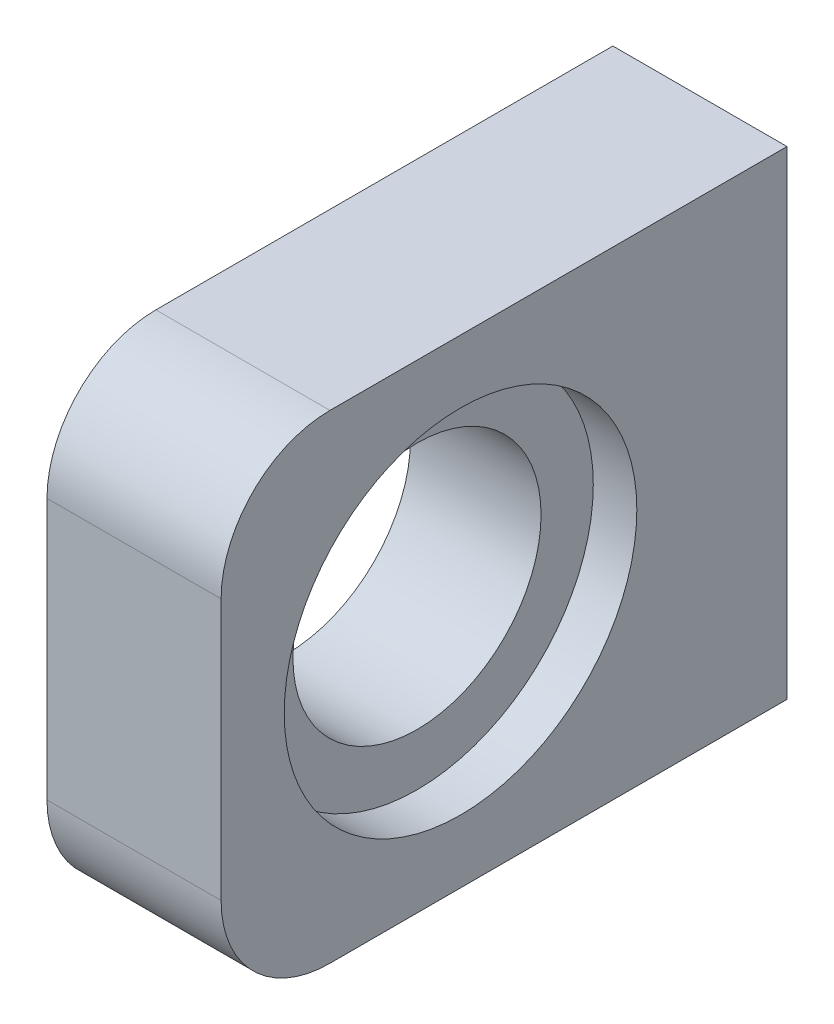
SolidWorks part; units mm, degrees
material "6061 Alloy"
ref_plane "Front Plane" through (0, 0, 0) normal (0, 0, 1) x (1, 0, 0)
ref_plane "Top Plane" through (0, 0, 0) normal (0, 1, 0) x (1, 0, 0)
ref_plane "Right Plane" through (0, 0, 0) normal (1, 0, 0) x (0, 0, -1)
ref_plane "Plane1" through (8, 0, 0) normal (1, 0, 0) x (0, 0, -1)
sketch "Sketch1" plane through (8, 0, 0) normal (1, 0, 0) x (0, 0, -1)
  line L0 (-22, 22) -> (-22, 0)
  line L1 (-22, 0) -> (4, 0)
  line L2 (4, 0) -> (4, 22)
  line L3 (4, 22) -> (-22, 22)
extrude "Boss-Extrude1" add sketch "Sketch1" against normal blind 8
sketch "Sketch2" plane through (8, 0, 0) normal (1, 0, 0) x (0, 0, -1)
  line L0 (-22, 22) -> (-22, 0) construction
  circle A0 centre (-11, 11) radius 8.1
  point P4 (-22, 11)
  dimension "D1" = 11
extrude "Cut-Extrude1" cut sketch "Sketch2" against normal blind 2
hole_wizard "M4x0.7 Tapped Hole1" positions "Sketch4" profile "Sketch3" tap size "M4x0.7" standard "ANSI Metric"
sketch "Sketch4" plane through (0, 0, -4) normal (0, 0, -1) x (-1, 0, 0)
  point P0 (-4, 16)
  point P1 (-4, 6)
sketch "Sketch3" plane through (4, 16, -4) normal (1, 0, 0) x (0, 1, 0)
  line L0 (0, 0) -> (0, 6.9914)
  line L1 (0, 6.9914) -> (1.65, 6)
  line L2 (1.65, 6) -> (1.65, 0)
  line L5 (1.65, 0) -> (0, 0)
  line L10 (0, 6.9914) -> (-1.65, 6) construction
  line L11 (0, -6.35) -> (0, 107.95) construction
  dimension "Tap Drill Dia." = 3.3
  dimension "Tap Drill Depth" = 6
  dimension "Drill Angle" = 118
hole_wizard "M10 Clearance Hole1" positions "Sketch6" profile "Sketch5" hole size "M10" standard "ANSI Metric" end condition through all
sketch "Sketch6" plane through (6, 0, 0) normal (1, 0, 0) x (0, 0, -1)
  point P0 (-11, 11)
sketch "Sketch5" plane through (6, 11, 11) normal (0, 1, 0) x (0, 0, -1)
  line L0 (0, 0) -> (0, 6)
  line L1 (0, 6) -> (5.7, 6)
  line L2 (5.7, 6) -> (5.7, 0)
  line L5 (5.7, 0) -> (0, 0)
  line L11 (0, -6.35) -> (0, 107.95) construction
  dimension "Thru Hole Dia." = 11.4
  dimension "Thru Hole Depth" = 6
fillet "Fillet1" radius 5 2 edges at (4, 22, 22) (4, 0, 22)
